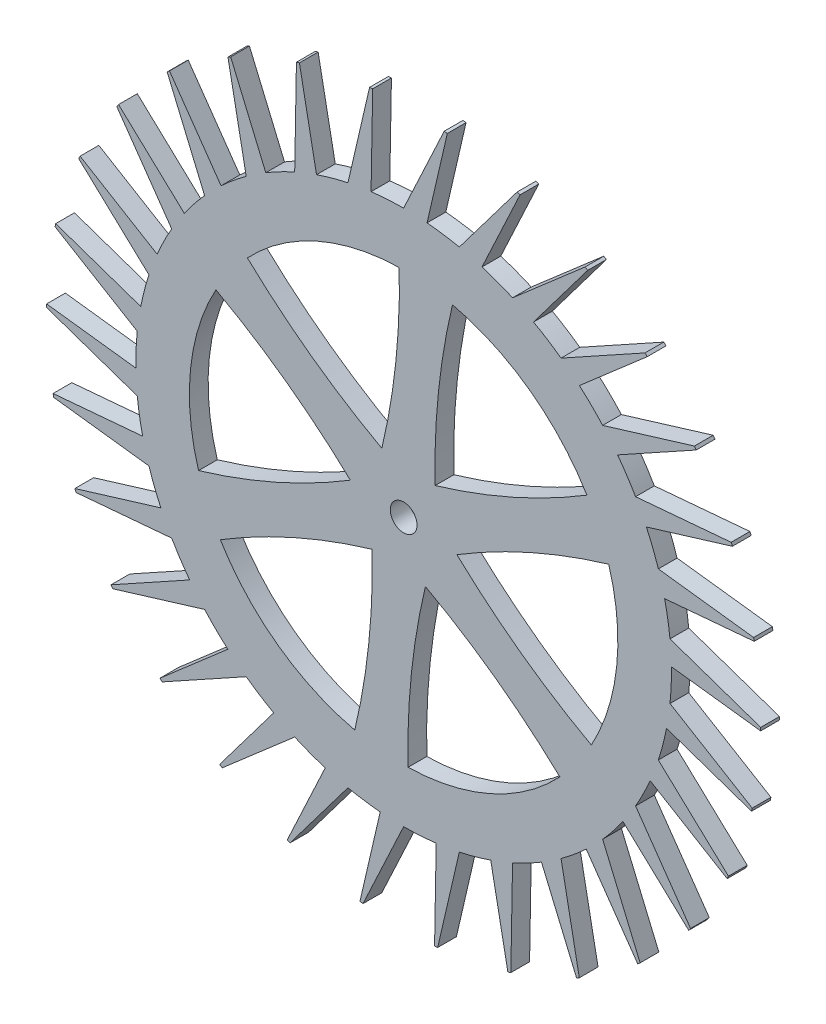
SolidWorks part; units mm, degrees
material "Cedar"
ref_plane "Front Plane" through (0, 0, 0) normal (0, 0, 1) x (1, 0, 0)
ref_plane "Top Plane" through (0, 0, 0) normal (0, 1, 0) x (1, 0, 0)
ref_plane "Right Plane" through (0, 0, 0) normal (1, 0, 0) x (0, 0, -1)
sketch "Sketch1" plane through (0, 0, 0) normal (0, 0, 1) x (1, 0, 0)
  circle A0 centre (0, 0) radius 63.5
  dimension "D1" = 127
extrude "Boss-Extrude1" add sketch "Sketch1" along normal blind 4.445
sketch "Sketch2" plane through (0, 0, 4.445) normal (0, 0, 1) x (1, 0, 0)
  line L0 (0, 0) -> (0, 84.6666)
  line L1 (0, 0) -> (17.6032, 82.8164)
  line L2 (0, 63.5) -> (9.6267, 84.1175)
  line L3 (9.6267, 84.1175) -> (10.3604, 84.0303)
  line L4 (10.3604, 84.0303) -> (5.5534, 63.2567)
  line L5 (10.3604, 84.0303) -> (0, 0)
  circle A0 centre (0, 0) radius 84.6666
  circle A1 centre (0, 0) radius 63.5 construction
  arc A2 (0, 63.5) -> (5.5534, 63.2567) centre (0, 0) cw
  point P3 (0, 63.5)
  circle M1 centre (0, 0) radius 63.5
  dimension "D1" = 169.3332
  dimension "D2" = 12
  dimension "D3" = 0.5
  dimension "D4" = 6
  dimension "D5" = 12
extrude "Boss-Extrude2" add sketch "Sketch2" against normal blind 4.445 contours L4 L3 L2 M1
pattern_circular "CirPattern1" count 30 every 12 about axis through (0, 0, 0) along (0, 0, 1) of "Boss-Extrude2"
sketch "Sketch3" plane through (0, 0, 4.445) normal (0, 0, 1) x (1, 0, 0)
  circle A0 centre (0, 0) radius 3.175
  dimension "D1" = 6.35
extrude "Cut-Extrude1" cut sketch "Sketch3" against normal through all
sketch "Sketch4" plane through (0, 0, 4.445) normal (0, 0, 1) x (1, 0, 0)
  line L0 (-1.0468, 50.7892) -> (-5.1656, 11.602)
  line L1 (-1.0468, 50.7892) -> (11.5836, 49.4617)
  line L2 (-5.1656, 11.602) -> (7.4649, 10.2745)
  line L3 (11.5836, 49.4617) -> (7.4649, 10.2745)
  line L4 (0, 0) -> (0, 63.5)
  line L5 (0, 0) -> (6.6376, 63.1521)
  circle A0 centre (0, 0) radius 12.7
  circle A1 centre (0, 0) radius 50.8
  arc A2 (-5.1656, 11.602) -> (-1.0468, 50.7892) centre (-154.4524, 47.1028) ccw
  arc A3 (7.4649, 10.2745) -> (11.5836, 49.4617) centre (160.8705, 13.961) cw
  arc A4 (7.4649, 10.2745) -> (43.4613, 26.3012) centre (-36.434, 157.3111) ccw
  arc A5 (12.6304, -1.3275) -> (48.6269, 14.6991) centre (92.5258, -132.3375) cw
  arc A6 (12.6304, -1.3275) -> (44.5082, -24.488) centre (118.0184, 110.2084) ccw
  arc A7 (5.1656, -11.602) -> (37.0433, -34.7626) centre (-68.3447, -146.2984) cw
  arc A8 (5.1656, -11.602) -> (1.0468, -50.7892) centre (154.4524, -47.1028) ccw
  arc A9 (-7.4649, -10.2745) -> (-11.5836, -49.4617) centre (-160.8705, -13.961) cw
  arc A10 (-7.4649, -10.2745) -> (-43.4613, -26.3012) centre (36.434, -157.3111) ccw
  arc A11 (-12.6304, 1.3275) -> (-48.6269, -14.6991) centre (-92.5258, 132.3375) cw
  arc A12 (-12.6304, 1.3275) -> (-44.5082, 24.488) centre (-118.0184, -110.2084) ccw
  arc A13 (-5.1656, 11.602) -> (-37.0433, 34.7626) centre (68.3447, 146.2984) cw
  arc A14 (13.2024, 62.1124) -> (5.5534, 63.2567) centre (0, 0) ccw construction
  point P6 (5.2684, 50.1255)
  point P8 (-1.8431, 31.0629)
  point P9 (8.2612, 30.0009)
  point P45 (0, 0)
  dimension "D1" = 25.4
  dimension "D2" = 101.6
  dimension "D4" = 10.16
  dimension "D3" = 12.7
  dimension "D6" = 6
  dimension "D5" = 6
extrude "Cut-Extrude2" cut sketch "Sketch4" against normal through all contours A13 L0 A1 | A11 A12 A1 | A9 A10 A1 | A7 A8 A1 | A5 A6 A1 | L3 A4 A1 | L0 A2 | A3 L3
